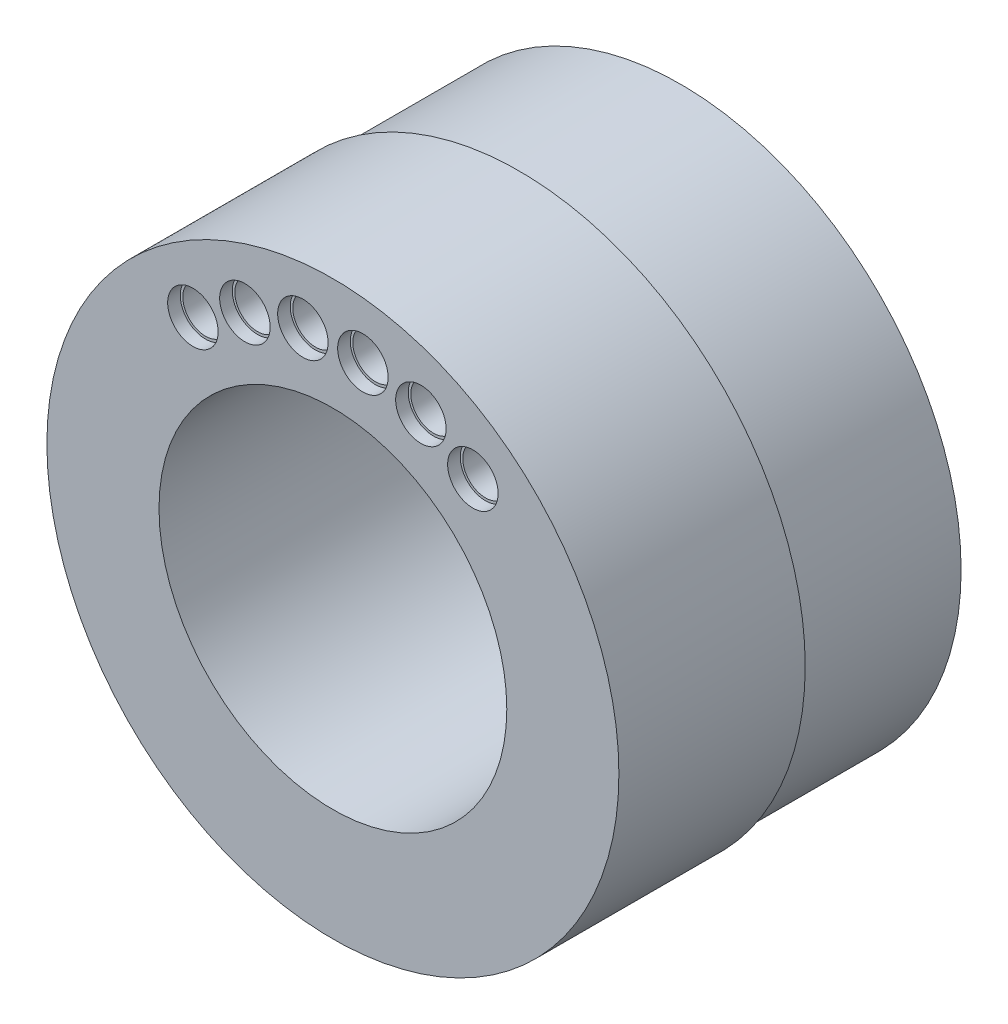
SolidWorks part; units mm, degrees
material "PET"
ref_plane "Front Plane" through (0, 0, 0) normal (0, 0, 1) x (1, 0, 0)
ref_plane "Top Plane" through (0, 0, 0) normal (0, 1, 0) x (1, 0, 0)
ref_plane "Right Plane" through (0, 0, 0) normal (1, 0, 0) x (0, 0, -1)
sketch "Sketch1" plane through (0, 0, 0) normal (0, 1, 0) x (1, 0, 0)
  line L0 (23.025, -13) -> (0, -13)
  line L1 (0, -13) -> (0, -28)
  line L2 (0, -28) -> (23.025, -28)
  line L3 (23.025, -28) -> (23.025, -13)
  line L4 (0, -13) -> (0, -28) construction
revolve "Revolve1" add sketch "Sketch1" angle 360 about L4
sketch "Sketch2" plane through (0, 0, 13) normal (0, 0, -1) x (-1, 0, 0)
  circle A0 centre (0, 0) radius 22.575
extrude "Boss-Extrude1" add sketch "Sketch2" along normal blind 13
hole_wizard "Hole1" positions "Sketch4" profile "Sketch3" legacy
sketch "Sketch4" plane through (0, 0, 28) normal (0, 0, 1) x (1, 0, 0)
  point P0 (0, 0)
sketch "Sketch3" plane through (0, 0, 28) normal (1, 0, 0) x (0, -1, 0)
  line L0 (0, 0) -> (0, 28)
  line L1 (0, 28) -> (10, 28)
  line L2 (10, 28) -> (10, 27)
  line L3 (10, 27) -> (14, 27)
  line L4 (14, 27) -> (14, 0)
  line L5 (14, 0) -> (0, 0)
  line L6 (0, 110) -> (0, -10) construction
  dimension "Diameter" = 20
  dimension "Depth" = 28
  dimension "C-Bore Diameter" = 28
  dimension "C-Bore Depth" = 27
hole_wizard "M2 Clearance Hole1" positions "Sketch6" profile "Sketch5" hole size "M2" standard "ANSI Metric"
sketch "Sketch6" plane through (0, 0, 0) normal (0, 0, -1) x (-1, 0, 0)
  point P0 (0, 17.5)
  point P1 (-17.5, 0)
  point P2 (0, -17.5)
  point P3 (17.5, 0)
sketch "Sketch5" plane through (0, 17.5, 0) normal (1, 0, 0) x (0, 1, 0)
  line L0 (0, 0) -> (0, 15.7388)
  line L1 (0, 15.7388) -> (1.2295, 15)
  line L2 (1.2295, 15) -> (1.2295, 0)
  line L5 (1.2295, 0) -> (0, 0)
  line L10 (0, 15.7388) -> (-1.2295, 15) construction
  line L11 (0, -6.35) -> (0, 107.95) construction
  dimension "Hole Dia." = 2.459
  dimension "Hole Depth" = 15
  dimension "Drill Angle" = 118
sketch "Sketch7" plane through (0, 0, 28) normal (0, 0, 1) x (1, 0, 0)
  line L0 (0, 0) -> (0, 35.679) construction
  line L1 (0, -15.4) -> (0, 15.4) construction
  line L2 (0, 0) -> (-2.4164, 18.3541) construction
  line L3 (-23.025, 0) -> (-14, 0) construction
  line L4 (15.4, 0) -> (-15.4, 0) construction
  line L5 (0, 0) -> (-7.0844, 17.1033) construction
  line L6 (-11.2697, 14.687) -> (0, 0) construction
  circle A0 centre (-2.4164, 18.3541) radius 1.8288
  circle A1 centre (0, 0) radius 18.5125 construction
  circle A2 centre (0, 0) radius 23.025 construction
  circle A3 centre (0, 0) radius 14 construction
  circle A4 centre (-7.0844, 17.1033) radius 1.8288
  circle A5 centre (-11.2697, 14.687) radius 1.8288
  circle A6 centre (11.2697, 14.687) radius 1.8288
  circle A7 centre (7.0844, 17.1033) radius 1.8288
  circle A8 centre (2.4164, 18.3541) radius 1.8288
  point P16 (-18.5125, 0)
  dimension "D1" = 3.6576
  dimension "D5" = 37.025
  dimension "D2" = 7.5
  dimension "D3" = 15
  dimension "D4" = 15
extrude "Cut-Extrude1" cut sketch "Sketch7" against normal blind 11.557
sketch "Sketch8" plane through (0, 0, 28) normal (0, 0, 1) x (1, 0, 0)
  circle A0 centre (-11.2697, 14.687) radius 2.032
  circle A1 centre (-7.0844, 17.1033) radius 2.032
  circle A2 centre (-2.4164, 18.3541) radius 2.032
  circle A3 centre (2.4164, 18.3541) radius 2.032
  circle A4 centre (7.0844, 17.1033) radius 2.032
  circle A5 centre (11.2697, 14.687) radius 2.032
  dimension "D1" = 4.064
extrude "Cut-Extrude2" cut sketch "Sketch8" against normal blind 1.016
